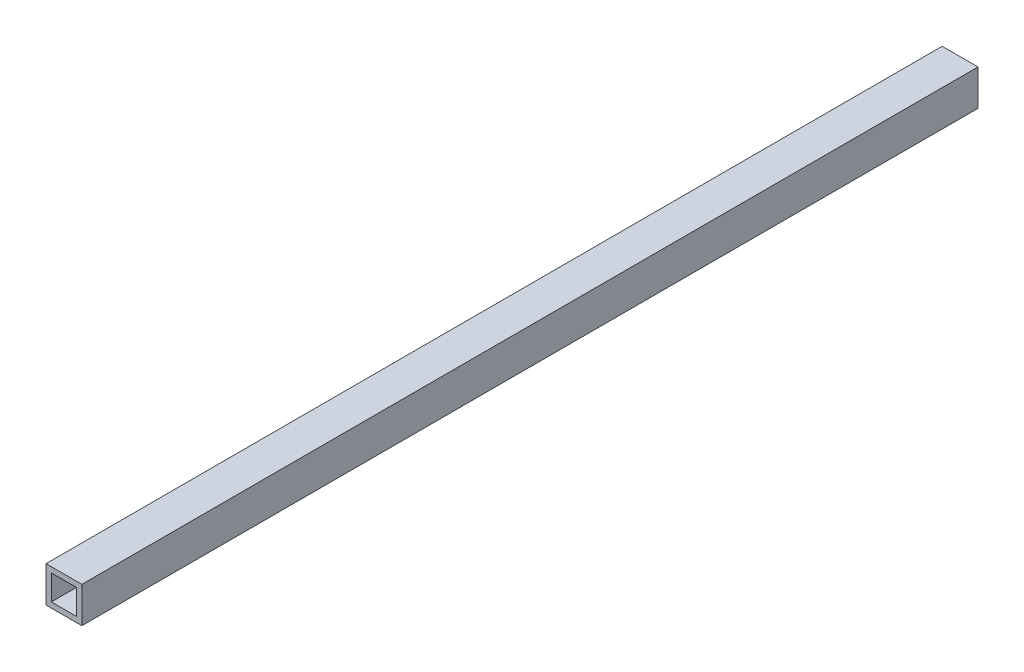
SolidWorks part; units mm, degrees
ref_plane "前视基准面" through (0, 0, 0) normal (0, 0, 1) x (1, 0, 0)
ref_plane "上视基准面" through (0, 0, 0) normal (0, 1, 0) x (1, 0, 0)
ref_plane "右视基准面" through (0, 0, 0) normal (1, 0, 0) x (0, 0, -1)
other "Configuration Table"
sketch "草图1" plane through (0, 0, 0) normal (0, 0, 1) x (1, 0, 0)
  line L0 (-3.5, 3.5) -> (-3.5, -3.5)
  line L1 (-5, 5) -> (5, 5)
  line L2 (-5, 5) -> (-5, -5)
  line L3 (-5, -5) -> (5, -5)
  line L4 (5, 5) -> (5, -5)
  line L5 (0, -5) -> (0, 5) construction
  line L6 (-5, 0) -> (5, 0) construction
  line L7 (-3.5, -3.5) -> (3.5, -3.5)
  line L8 (3.5, 3.5) -> (3.5, -3.5)
  line L9 (-3.5, 3.5) -> (3.5, 3.5)
  point P0 (0, 0)
  dimension "D1" = 10
  dimension "D2" = 1.5
extrude "凸台-拉伸1" add sketch "草图1" along normal blind 250
